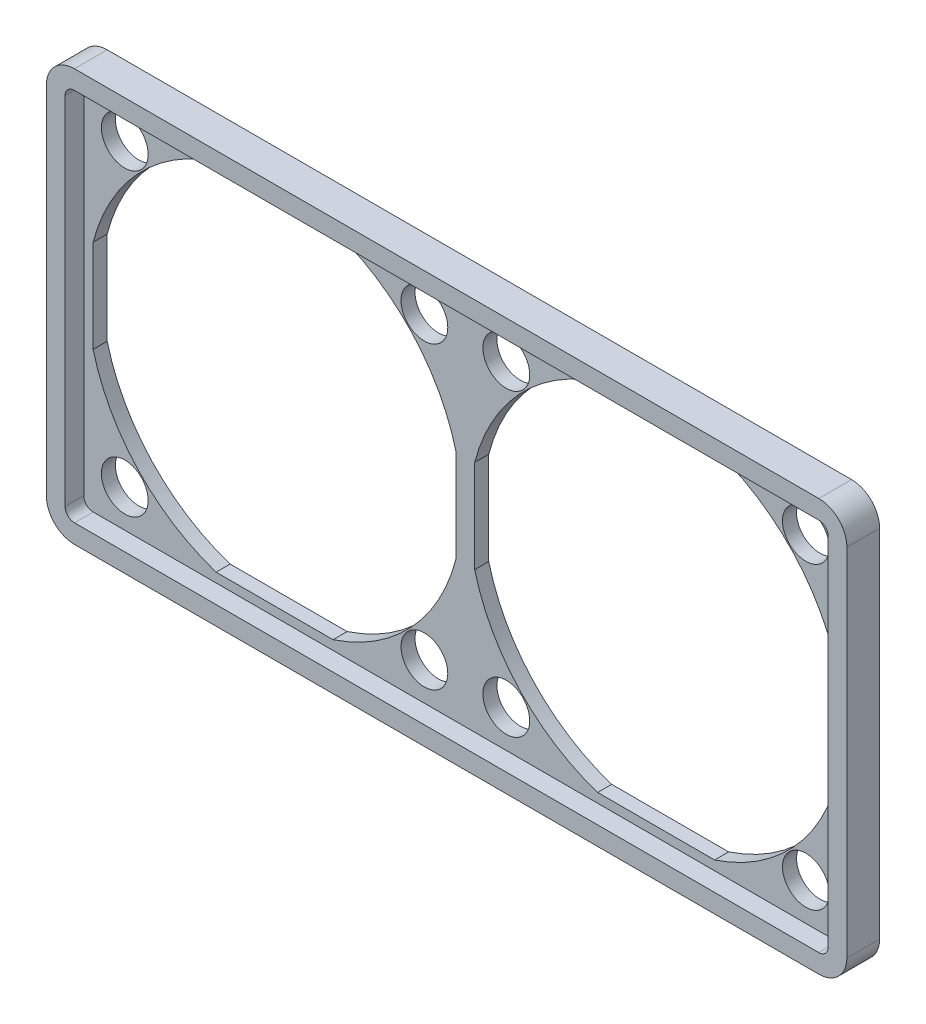
SolidWorks part; units mm, degrees
ref_plane "Front Plane" through (0, 0, 0) normal (0, 0, 1) x (1, 0, 0)
ref_plane "Top Plane" through (0, 0, 0) normal (0, 1, 0) x (1, 0, 0)
ref_plane "Right Plane" through (0, 0, 0) normal (1, 0, 0) x (0, 0, -1)
sketch "Sketch1" plane through (0, 0, 0) normal (0, 0, 1) x (1, 0, 0)
  line L0 (0, 20) -> (-40.75, -20) construction
  line L1 (39.75, 20) -> (-39.75, 20)
  line L2 (0, 20) -> (0, -20) construction
  line L3 (39.75, -20) -> (-39.75, -20)
  line L4 (-40.75, 19) -> (-40.75, -19)
  line L5 (40.75, 19) -> (40.75, -19)
  line L6 (26.62, 19) -> (14.13, 19)
  line L7 (-39.75, 4.9608) -> (-39.75, -4.9608)
  line L8 (26.62, -19) -> (14.13, -19)
  line L9 (39.75, 4.9608) -> (39.75, -4.9608)
  line L10 (-1, 4.9608) -> (-1, -4.9608)
  line L11 (1, 4.9608) -> (1, -4.9608)
  line L12 (-14.13, 19) -> (-26.62, 19)
  line L13 (1, 20) -> (1, -20) construction
  line L14 (-1, 20) -> (-1, -20) construction
  line L15 (-14.13, -19) -> (-26.62, -19)
  line L16 (39.75, 19) -> (-39.75, 19) construction
  line L17 (-39.75, 19) -> (-39.75, -19) construction
  line L18 (39.75, -19) -> (-39.75, -19) construction
  line L19 (40.75, 20) -> (-40.75, 20) construction
  line L20 (39.75, 19) -> (39.75, -19) construction
  line L21 (-40.75, 20) -> (-40.75, -20) construction
  line L22 (40.75, -20) -> (-40.75, -20) construction
  line L23 (40.75, 20) -> (40.75, -20) construction
  arc A0 (-26.62, 19) -> (-39.75, 4.9608) centre (-20.375, 0) ccw
  circle A1 centre (-36.375, 16) radius 2.5
  circle A2 centre (-4.375, 16) radius 2.5
  circle A3 centre (-4.375, -16) radius 2.5
  circle A4 centre (-36.375, -16) radius 2.5
  circle A5 centre (36.375, -16) radius 2.5
  circle A6 centre (4.375, -16) radius 2.5
  circle A7 centre (4.375, 16) radius 2.5
  circle A8 centre (36.375, 16) radius 2.5
  arc A9 (1, 4.9608) -> (14.13, 19) centre (20.375, 0) cw
  arc A10 (-39.75, -4.9608) -> (-26.62, -19) centre (-20.375, 0) ccw
  arc A11 (-14.13, -19) -> (-1, -4.9608) centre (-20.375, 0) ccw
  arc A12 (-1, 4.9608) -> (-14.13, 19) centre (-20.375, 0) ccw
  arc A13 (14.13, -19) -> (1, -4.9608) centre (20.375, 0) cw
  arc A14 (39.75, -4.9608) -> (26.62, -19) centre (20.375, 0) cw
  arc A15 (26.62, 19) -> (39.75, 4.9608) centre (20.375, 0) cw
  arc A16 (-39.75, 20) -> (-40.75, 19) centre (-39.75, 19) ccw
  arc A17 (-39.75, -20) -> (-40.75, -19) centre (-39.75, -19) cw
  arc A18 (40.75, -19) -> (39.75, -20) centre (39.75, -19) cw
  arc A19 (40.75, 19) -> (39.75, 20) centre (39.75, 19) ccw
  point P6 (0, 0)
  point P9 (-20.375, 0)
  point P19 (-20.375, 0)
  point P55 (-40.75, 20)
  dimension "D1" = 1
  dimension "D3" = 5
  dimension "D9" = 1
  dimension "D2" = 40.75
  dimension "D5" = 32
  dimension "D6" = 40
  dimension "D7" = 1
  dimension "D8" = 1
  dimension "D4" = 4
extrude "Boss-Extrude1" add sketch "Sketch1" along normal blind 1.5
sketch "Sketch2" plane through (0, 0, 0) normal (0, 0, -1) x (-1, 0, 0)
  line L0 (39.75, 22) -> (-39.75, 22)
  line L1 (-42.75, 19) -> (-42.75, -19)
  line L2 (-39.75, -22) -> (39.75, -22)
  line L3 (42.75, -19) -> (42.75, 19)
  line L4 (40.75, -19) -> (40.75, 19)
  line L5 (-39.75, -20) -> (39.75, -20)
  line L6 (-40.75, 19) -> (-40.75, -19)
  line L7 (39.75, 20) -> (-39.75, 20)
  line L8 (40.75, -19) -> (40.75, 19)
  line L9 (-39.75, -20) -> (39.75, -20)
  line L10 (-40.75, 19) -> (-40.75, -19)
  line L11 (39.75, 20) -> (-39.75, 20)
  arc A0 (42.75, 19) -> (39.75, 22) centre (39.75, 19) ccw
  arc A1 (-39.75, 22) -> (-42.75, 19) centre (-39.75, 19) ccw
  arc A2 (-42.75, -19) -> (-39.75, -22) centre (-39.75, -19) ccw
  arc A3 (39.75, -22) -> (42.75, -19) centre (39.75, -19) ccw
  arc A4 (40.75, 19) -> (39.75, 20) centre (39.75, 19) ccw
  arc A5 (39.75, -20) -> (40.75, -19) centre (39.75, -19) ccw
  arc A6 (-40.75, -19) -> (-39.75, -20) centre (-39.75, -19) ccw
  arc A7 (-39.75, 20) -> (-40.75, 19) centre (-39.75, 19) ccw
  arc A8 (40.75, 19) -> (39.75, 20) centre (39.75, 19) ccw
  arc A9 (39.75, -20) -> (40.75, -19) centre (39.75, -19) ccw
  arc A10 (-40.75, -19) -> (-39.75, -20) centre (-39.75, -19) ccw
  arc A11 (-39.75, 20) -> (-40.75, 19) centre (-39.75, 19) ccw
  dimension "D1" = 0
  dimension "D2" = 2
extrude "Boss-Extrude2" add sketch "Sketch2" against normal blind 3.5
